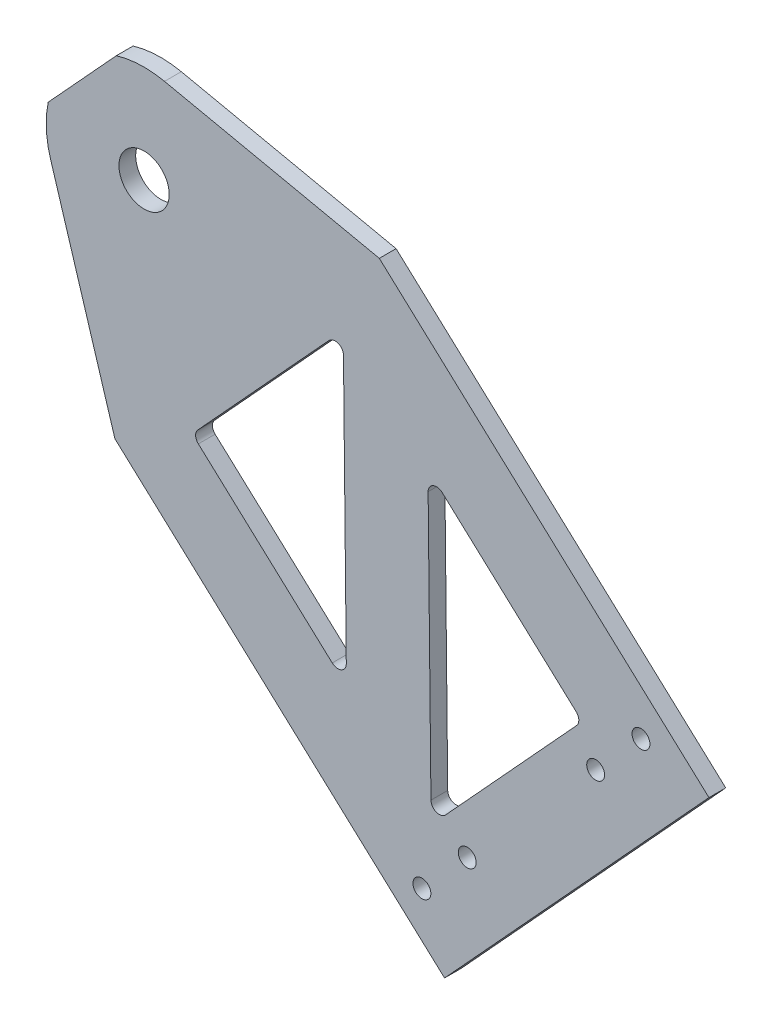
SolidWorks part; units mm, degrees
material "Thornel Mat VMA"
ref_plane "前视基准面" through (0, 0, 0) normal (0, 0, 1) x (1, 0, 0)
ref_plane "上视基准面" through (0, 0, 0) normal (0, 1, 0) x (1, 0, 0)
ref_plane "右视基准面" through (0, 0, 0) normal (1, 0, 0) x (0, 0, -1)
sketch "草图1" plane through (0, 0, 0) normal (0, 0, 1) x (1, 0, 0)
  line L0 (-329.5739, -130.8851) -> (-282.2748, -79.2829)
  line L1 (-329.5739, -130.8851) -> (-403.2914, -63.3149)
  line L2 (-282.2748, -79.2829) -> (-355.9922, -11.7127)
  line L3 (-404.5208, -35.0574) -> (-384.2497, -12.9421)
  line L12 (-403.2914, -63.3149) -> (-404.5208, -35.0574)
  line L13 (-355.9922, -11.7127) -> (-384.2497, -12.9421)
  line L14 (-333.6286, -119.0294) -> (-294.4379, -76.2733) construction
  line L15 (-394.3853, -23.9997) -> (-383.3277, -34.1353) construction
  circle A12 centre (-383.3277, -34.1353) radius 4.5
  circle A13 centre (-333.6286, -119.0294) radius 1.6
  circle A14 centre (-325.5202, -110.1833) radius 1.6
  circle A15 centre (-302.5463, -85.1194) radius 1.6
  circle A16 centre (-294.4379, -76.2733) radius 1.6
  point P3 (-390.3181, -27.7278)
  point P4 (-370.7357, 1.8014)
  point P5 (-418.0349, -49.8008)
  point P8 (0, 0)
  point P9 (0, 0)
  point P10 (0, 0)
  point P11 (-345.0631, -132.5368)
  point P12 (0, 0)
  point P36 (-382.9456, -14.6611)
  dimension "D14" = 9
  dimension "D15" = 3.2
  dimension "D19" = 6
  dimension "D20" = 6
  dimension "D1" = 120
  dimension "D3" = 70
  dimension "D4" = 15
  dimension "D16" = 11
  dimension "D17" = 12
  dimension "D18" = 12
extrude "凸台-拉伸1" add sketch "草图1" along normal blind 3
sketch "Sketch1" plane through (0, 0, 3) normal (0, 0, 1) x (1, 0, 0)
  line L0 (-400.0597, -39.2626) -> (-388.5479, -76.8289)
  line L1 (-403.2914, -63.3149) -> (-329.5739, -130.8851) construction
  line L2 (-388.5479, -76.8289) -> (-341.2487, -25.2267) construction
  line L3 (-282.2748, -79.2829) -> (-355.9922, -11.7127) construction
  line L4 (-341.2487, -25.2267) -> (-379.6729, -17.0212)
  line L5 (-388.5479, -76.8289) -> (-464.1283, -22.5269)
  line L6 (-464.1283, -22.5269) -> (-423.3761, 22.6845)
  line L7 (-423.3761, 22.6845) -> (-334.9351, 6.8296)
  line L8 (-334.9351, 6.8296) -> (-341.2487, -25.2267)
  line L15 (-373.6207, -70.1634) -> (-349.6683, -92.1184)
  line L16 (-347.1548, -90.9968) -> (-347.6582, -43.4594)
  line L17 (-350.2639, -42.4617) -> (-373.7129, -68.0441)
  line L18 (-330.0004, -55.885) -> (-306.048, -77.8401)
  line L19 (-305.9558, -79.9594) -> (-329.4049, -105.5417)
  line L20 (-332.0106, -104.544) -> (-332.5139, -57.0067)
  line L21 (-329.5739, -130.8851) -> (-282.2748, -79.2829) construction
  line L22 (-282.2748, -79.2829) -> (-329.5739, -130.8851) construction
  arc A0 (-379.6729, -17.0212) -> (-400.0597, -39.2626) centre (-383.3277, -34.1353) ccw
  circle A2 centre (-302.5463, -85.1194) radius 1.6 construction
  arc A3 (-306.048, -77.8401) -> (-305.9558, -79.9594) centre (-307.0616, -78.9458) cw
  arc A4 (-330.0004, -55.885) -> (-332.5139, -57.0067) centre (-331.014, -56.9908) ccw
  arc A5 (-329.4049, -105.5417) -> (-332.0106, -104.544) centre (-330.5107, -104.5282) cw
  arc A6 (-349.6683, -92.1184) -> (-347.1548, -90.9968) centre (-348.6548, -91.0127) ccw
  arc A7 (-373.6207, -70.1634) -> (-373.7129, -68.0441) centre (-372.6072, -69.0576) cw
  arc A8 (-347.6582, -43.4594) -> (-350.2639, -42.4617) centre (-349.1581, -43.4753) ccw
  circle A15 centre (-383.3277, -34.1353) radius 4.5 construction
  point P27 (-330.1911, -103.4304)
  point P28 (-315.5233, -88.8029)
  point P33 (0, 0)
  point P34 (-341.0209, -104.1144)
  point P35 (0, 0)
  point P36 (0, 0)
  point P39 (-320.876, -60.1367)
  point P40 (0, 0)
  point P53 (-347.6984, -39.6629)
  dimension "D1" = 35
  dimension "D12" = 1.5
  dimension "D2" = 25
  dimension "D3" = 75
  dimension "D6" = 15
  dimension "D8" = 15
  dimension "D9" = 15
  dimension "D10" = 6
extrude "Cut-Extrude1" cut sketch "Sketch1" against normal blind 3
